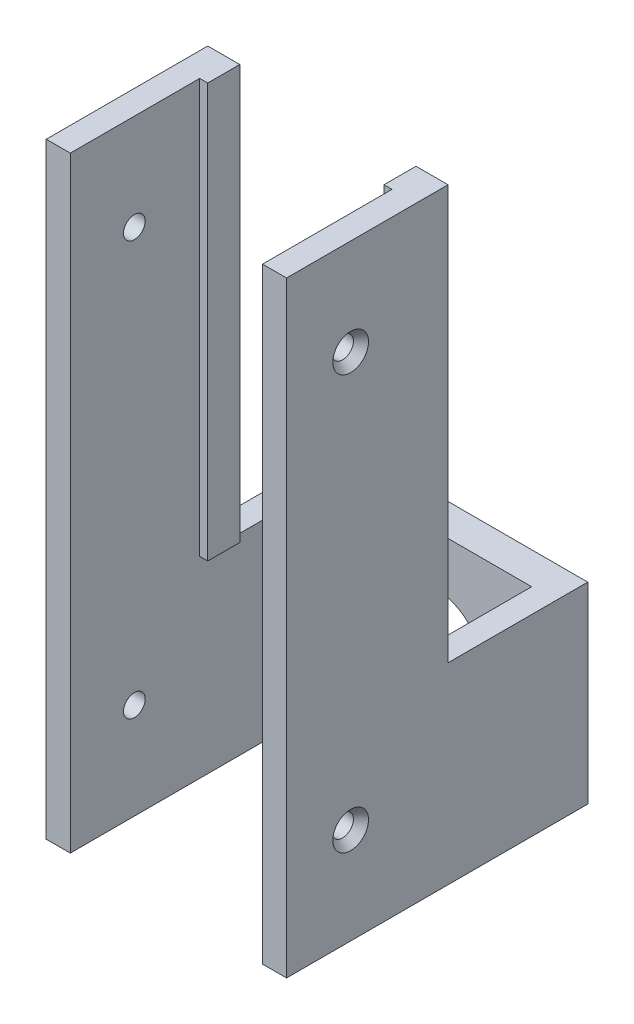
SolidWorks part; units mm, degrees
ref_plane "Front Plane" through (0, 0, 0) normal (0, 0, 1) x (1, 0, 0)
ref_plane "Top Plane" through (0, 0, 0) normal (0, 1, 0) x (1, 0, 0)
ref_plane "Right Plane" through (0, 0, 0) normal (1, 0, 0) x (0, 0, -1)
sketch "Sketch1" plane through (0, 0, 0) normal (0, 1, 0) x (1, 0, 0)
  line L0 (0, 0) -> (0, 59.69)
  line L1 (0, 59.69) -> (47.625, 59.69)
  line L2 (47.625, 59.69) -> (47.625, 0)
  line L3 (47.625, 0) -> (42.8625, 0)
  line L4 (42.8625, 0) -> (42.8625, 53.34)
  line L5 (42.8625, 53.34) -> (4.7625, 53.34)
  line L6 (4.7625, 53.34) -> (4.7625, 0)
  line L7 (4.7625, 0) -> (0, 0)
  dimension "D1" = 38.1
  dimension "D2" = 4.7625
  dimension "D3" = 53.34
  dimension "D4" = 6.35
  dimension "D5" = 4.7625
extrude "Boss-Extrude1" add sketch "Sketch1" along normal blind 38.1
sketch "Sketch3" plane through (0, 0, 0) normal (-1, 0, 0) x (0, 0, 1)
  line L0 (-59.69, 38.1) -> (-25.654, 38.1) construction
  line L1 (0, 120.142) -> (0, 0) construction
  line L2 (-25.654, 120.142) -> (0, 120.142) construction
  line L3 (0, 120.142) -> (0, 0) construction
  point P0 (-12.7, 19.05)
  point P5 (-12.7, 101.092)
  dimension "D1" = 19.05
  dimension "D2" = 12.7
  dimension "D3" = 19.05
  dimension "D4" = 12.7
sketch "Sketch5" plane through (47.625, 0, 0) normal (1, 0, 0) x (0, 0, -1)
  line L0 (0, 120.142) -> (0, 0) construction
  line L1 (25.654, 38.1) -> (59.69, 38.1) construction
  line L2 (0, 120.142) -> (0, 0) construction
  line L3 (0, 120.142) -> (25.654, 120.142) construction
  point P0 (12.7, 19.05)
  point P7 (12.7, 101.092)
  dimension "D1" = 12.7
  dimension "D2" = 19.05
  dimension "D3" = 12.7
  dimension "D4" = 19.05
sketch "Sketch7" plane through (0, 0, -59.69) normal (0, 0, -1) x (-1, 0, 0)
  line L0 (-47.625, 38.1) -> (0, 38.1) construction
  line L1 (-47.625, 38.1) -> (-47.625, 0) construction
  circle A0 centre (-23.8125, 19.05) radius 9.2075
  dimension "D1" = 18.415
  dimension "D2" = 19.05
  dimension "D3" = 23.8125
extrude "Cut-Extrude2" cut sketch "Sketch7" against normal blind 38.1
sketch "Sketch8" plane through (0, 38.1, 0) normal (0, 1, 0) x (1, 0, 0)
  line L0 (0, 59.69) -> (0, 0) construction
  line L1 (0, 25.654) -> (4.7625, 25.654)
  line L2 (0, 25.654) -> (0, 0)
  line L3 (0, 0) -> (4.7625, 0)
  line L4 (4.7625, 25.654) -> (4.7625, 0)
  line L5 (42.8625, 53.34) -> (42.8625, 0) construction
  line L6 (42.8625, 25.654) -> (47.625, 25.654)
  line L7 (42.8625, 25.654) -> (42.8625, 0)
  line L8 (42.8625, 0) -> (47.625, 0)
  line L9 (47.625, 25.654) -> (47.625, 0)
  line L10 (47.625, 0) -> (47.625, 59.69) construction
  dimension "D1" = 25.654
  dimension "D2" = 25.654
extrude "Boss-Extrude2" add sketch "Sketch8" along normal blind 82.042
hole_wizard "CSK for #6 Flat Head Machine Screw1" positions "Sketch3" profile "Sketch4" countersink size "#6" standard "ANSI Inch"
sketch "Sketch4" plane through (0, 19.05, -12.7) normal (0, 1, 0) x (0, 0, 1)
  line L0 (0, 0) -> (0, 4.7625)
  line L1 (0, 4.7625) -> (2.1526, 4.7625)
  line L2 (2.1526, 4.7625) -> (2.1526, 1.5998)
  line L3 (2.1526, 1.5998) -> (3.5433, 0)
  line L5 (3.5433, 0) -> (0, 0)
  line L6 (-2.1526, 1.5998) -> (-3.5433, 0) construction
  line L11 (0, -6.35) -> (0, 107.95) construction
  dimension "Thru Hole Dia." = 4.3053
  dimension "Thru Hole Depth" = 4.7625
  dimension "Near C'Sink Dia." = 7.0866
  dimension "Near C'Sink Angle" = 82
hole_wizard "CSK for #6 Flat Head Machine Screw2" positions "Sketch5" profile "Sketch6" countersink size "#6" standard "ANSI Inch" end condition up to next
sketch "Sketch6" plane through (47.625, 19.05, -12.7) normal (0, 1, 0) x (0, 0, -1)
  line L0 (0, 0) -> (0, 4.7625)
  line L1 (0, 4.7625) -> (2.1526, 4.7625)
  line L2 (2.1526, 4.7625) -> (2.1526, 1.5998)
  line L3 (2.1526, 1.5998) -> (3.5433, 0)
  line L5 (3.5433, 0) -> (0, 0)
  line L6 (-2.1526, 1.5998) -> (-3.5433, 0) construction
  line L11 (0, -6.35) -> (0, 107.95) construction
  dimension "Thru Hole Dia." = 4.3053
  dimension "Thru Hole Depth" = 4.7625
  dimension "Near C'Sink Dia." = 7.0866
  dimension "Near C'Sink Angle" = 82
sketch "Sketch9" plane through (0, 0, -25.654) normal (0, 0, -1) x (-1, 0, 0)
  line L0 (-4.7625, 120.142) -> (0, 120.142) construction
  line L1 (0, 120.142) -> (-6.35, 120.142)
  line L2 (0, 120.142) -> (0, 38.1)
  line L3 (0, 38.1) -> (-6.35, 38.1)
  line L4 (-6.35, 120.142) -> (-6.35, 38.1)
  line L5 (-47.625, 38.1) -> (0, 38.1) construction
  line L6 (-47.625, 120.142) -> (-42.8625, 120.142) construction
  line L7 (-47.625, 120.142) -> (-41.275, 120.142)
  line L8 (-47.625, 120.142) -> (-47.625, 38.1)
  line L9 (-47.625, 38.1) -> (-41.275, 38.1)
  line L10 (-41.275, 120.142) -> (-41.275, 38.1)
  line L11 (-47.625, 120.142) -> (-47.625, 38.1) construction
  line L12 (0, 120.142) -> (0, 38.1) construction
  dimension "D1" = 6.35
  dimension "D2" = 6.35
extrude "Boss-Extrude3" add sketch "Sketch9" along normal blind 6.35
